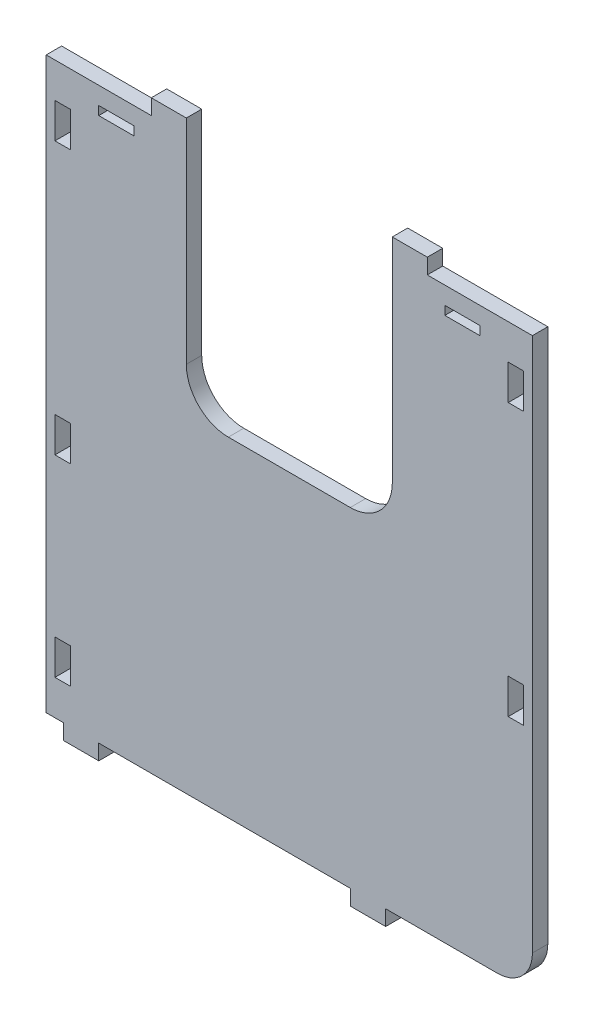
SolidWorks part; units mm, degrees
ref_plane "Front Plane" through (0, 0, 0) normal (0, 0, 1) x (1, 0, 0)
ref_plane "Top Plane" through (0, 0, 0) normal (0, 1, 0) x (1, 0, 0)
ref_plane "Right Plane" through (0, 0, 0) normal (1, 0, 0) x (0, 0, -1)
sketch "Sketch1" plane through (0, 0, 0) normal (0, 0, 1) x (1, 0, 0)
  line L0 (18.6626, 103.275) -> (-0.3874, 103.275)
  line L1 (-0.3874, 103.275) -> (-0.3874, 106.069)
  line L2 (-0.3874, 106.069) -> (-6.7374, 106.069)
  line L3 (-6.7374, 106.069) -> (-6.7374, 59.7823)
  line L4 (-50.4254, 103.275) -> (-69.4754, 103.275)
  line L5 (-69.4754, 103.275) -> (-69.4754, 0)
  line L6 (0, 0) -> (-50, 0) construction
  line L7 (-66.3004, 0) -> (-66.3004, -2.794)
  line L8 (-69.4754, -2.794) -> (-54.9339, -2.794) construction
  line L9 (-66.3004, -2.794) -> (-59.9504, -2.794)
  line L10 (-69.4754, 0) -> (-66.3004, 0)
  line L11 (18.6626, 0) -> (18.6626, 103.275)
  line L12 (-49.8539, -2.794) -> (-37.9495, -2.794) construction
  line L13 (17.0751, 90.575) -> (17.0751, 47.625) construction
  line L14 (17.0751, 103.275) -> (14.2811, 103.275) construction
  line L15 (-6.7374, 59.7823) -> (-44.0754, 59.7823)
  line L16 (-44.0754, 59.7823) -> (-44.0754, 106.069)
  line L17 (-44.0754, 106.069) -> (-50.4254, 106.069)
  line L18 (-50.4254, 106.069) -> (-50.4254, 103.275)
  line L20 (-59.9504, -2.794) -> (-59.9504, 0)
  line L21 (-14.2875, 0) -> (-14.2875, -2.794)
  line L22 (-4.1275, -2.794) -> (-12.8743, -2.794) construction
  line L23 (-14.2875, -2.794) -> (-7.9375, -2.794)
  line L24 (-7.9375, -2.794) -> (-7.9375, 0)
  line L25 (-59.9504, 0) -> (-14.2875, 0)
  line L26 (-7.9375, 0) -> (18.6626, 0)
  line L28 (-67.8879, 12.7) -> (-67.8879, 41.275) construction
  dimension "D1" = 1.5875
  dimension "D2" = 6.35
  dimension "D3" = 2.794
  dimension "D4" = 19.05
  dimension "D5" = 6.35
  dimension "D6" = 3.175
  dimension "D7" = 6.35
  dimension "D8" = 6.35
  dimension "D9" = 1.5875
extrude "Boss-Extrude1" add sketch "Sketch1" along normal blind 2.794 contours L10 L7 L9 L20 L25 L21 L23 L24 L26 L11 L0 L1 L2 L3 L15 L16 L17 L18 L4 L5
fillet "Fillet1" radius 7.62 2 edges at (-44.0754, 59.7823, 1.397) (-6.7374, 59.7823, 1.397)
sketch "Sketch2" plane through (0, 0, 2.794) normal (0, 0, 1) x (1, 0, 0)
  line L0 (-59.9504, 103.275) -> (-59.9504, 106.069) construction
  line L1 (-59.9504, 100.1) -> (-53.6004, 100.1)
  line L2 (-59.9504, 100.1) -> (-59.9504, 98.5125)
  line L3 (-59.9504, 98.5125) -> (-53.6004, 98.5125)
  line L4 (-53.6004, 100.1) -> (-53.6004, 98.5125)
  line L5 (2.7876, 100.1) -> (9.1376, 100.1)
  line L6 (2.7876, 100.1) -> (2.7876, 98.5125)
  line L7 (2.7876, 98.5125) -> (9.1376, 98.5125)
  line L8 (9.1376, 100.1) -> (9.1376, 98.5125)
  line L9 (-53.6004, 103.275) -> (-53.6004, 106.069) construction
  line L10 (-66.9354, 103.275) -> (16.1226, 103.275) construction
  line L11 (14.2811, 47.625) -> (14.2811, 41.275) construction
  line L12 (14.2811, 41.275) -> (17.0751, 41.275) construction
  line L13 (17.0751, 41.275) -> (17.0751, 47.625) construction
  line L14 (17.0751, 47.625) -> (14.2811, 47.625) construction
  line L15 (14.2811, 96.925) -> (14.2811, 90.575) construction
  line L16 (14.2811, 90.575) -> (17.0751, 90.575) construction
  line L17 (17.0751, 90.575) -> (17.0751, 96.925) construction
  line L18 (17.0751, 96.925) -> (14.2811, 96.925) construction
  line L19 (-65.0939, 90.575) -> (-65.0939, 96.925) construction
  line L20 (-65.0939, 96.925) -> (-67.8879, 96.925) construction
  line L21 (-67.8879, 96.925) -> (-67.8879, 90.575) construction
  line L22 (-67.8879, 90.575) -> (-65.0939, 90.575) construction
  line L23 (-65.0939, 41.275) -> (-65.0939, 47.625) construction
  line L24 (-65.0939, 47.625) -> (-67.8879, 47.625) construction
  line L25 (-67.8879, 47.625) -> (-67.8879, 41.275) construction
  line L26 (-67.8879, 41.275) -> (-65.0939, 41.275) construction
  line L27 (-65.0939, 6.35) -> (-65.0939, 12.7) construction
  line L28 (-65.0939, 12.7) -> (-67.8879, 12.7) construction
  line L29 (-67.8879, 12.7) -> (-67.8879, 6.35) construction
  line L30 (-67.8879, 6.35) -> (-65.0939, 6.35) construction
  line L31 (14.2811, 47.625) -> (14.2811, 41.275)
  line L32 (14.2811, 41.275) -> (17.0751, 41.275)
  line L33 (17.0751, 41.275) -> (17.0751, 47.625)
  line L34 (17.0751, 47.625) -> (14.2811, 47.625)
  line L35 (14.2811, 96.925) -> (14.2811, 90.575)
  line L36 (14.2811, 90.575) -> (17.0751, 90.575)
  line L37 (17.0751, 90.575) -> (17.0751, 96.925)
  line L38 (17.0751, 96.925) -> (14.2811, 96.925)
  line L39 (-65.0939, 90.575) -> (-65.0939, 96.925)
  line L40 (-65.0939, 96.925) -> (-67.8879, 96.925)
  line L41 (-67.8879, 96.925) -> (-67.8879, 90.575)
  line L42 (-67.8879, 90.575) -> (-65.0939, 90.575)
  line L43 (-65.0939, 41.275) -> (-65.0939, 47.625)
  line L44 (-65.0939, 47.625) -> (-67.8879, 47.625)
  line L45 (-67.8879, 47.625) -> (-67.8879, 41.275)
  line L46 (-67.8879, 41.275) -> (-65.0939, 41.275)
  line L47 (-65.0939, 6.35) -> (-65.0939, 12.7)
  line L48 (-65.0939, 12.7) -> (-67.8879, 12.7)
  line L49 (-67.8879, 12.7) -> (-67.8879, 6.35)
  line L50 (-67.8879, 6.35) -> (-65.0939, 6.35)
  dimension "D1" = 1.5875
  dimension "D2" = 3.175
  dimension "D3" = 6.35
  dimension "D4" = 3.175
  dimension "D5" = 1.5875
extrude "Cut-Extrude1" cut sketch "Sketch2" against normal through all
fillet "Fillet2" radius 6.35 1 edges at (18.6626, 0, 1.397)
equation "\"D1@Boss-Extrude1\"=\"thick@assy.sldasm\""
equation "\"D3@Sketch1\"=\"thick@assy.sldasm\""
